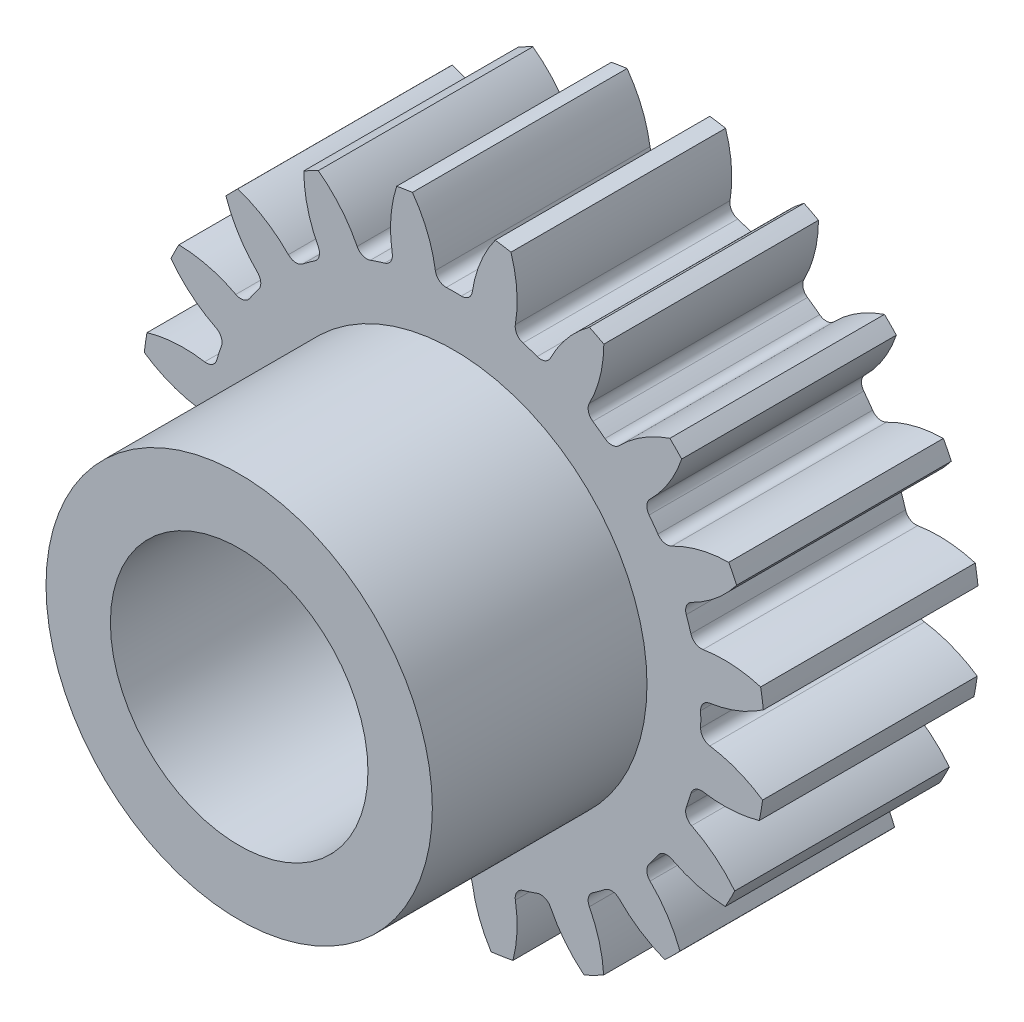
SolidWorks part; units mm, degrees
ref_plane "Front Plane" through (0, 0, 0) normal (0, 0, 1) x (1, 0, 0)
ref_plane "Top Plane" through (0, 0, 0) normal (0, 1, 0) x (1, 0, 0)
ref_plane "Right Plane" through (0, 0, 0) normal (1, 0, 0) x (0, 0, -1)
sketch "Sketch1" plane through (0, 0, 0) normal (0, 0, 1) x (1, 0, 0)
  circle A0 centre (0, 0) radius 3.63
  dimension "D1" = 7.26
extrude "Boss-Extrude1" add sketch "Sketch1" along normal blind 2.5
sketch "Sketch2" plane through (0, 0, 0) normal (0, 0, 1) x (1, 0, 0)
  line L0 (0, 47.3598) -> (0, -34.7567) construction
  line L1 (-0.2027, 2.8307) -> (0, 0) construction
  line L2 (0, 2.4405) -> (-2.4728, 9.2343) construction
  arc A0 (0.4819, 3.5979) -> (-0.4819, 3.5979) centre (0, 0) ccw
  arc A1 (0.3087, 3.2855) -> (-0.3087, 3.2855) centre (0, 0) ccw construction
  arc A2 (0.2027, 2.8307) -> (-0.2027, 2.8307) centre (0, 0) ccw
  arc A3 (-0.4819, 3.5979) -> (-0.2027, 2.8307) centre (-1.6885, 2.7243) cw
  arc A4 (0.4819, 3.5979) -> (0.2027, 2.8307) centre (1.6885, 2.7243) ccw
  point P12 (-0.2888, 3.2338)
  dimension "D1" = 7.26
  dimension "D2" = 6.6
  dimension "D3" = 0.792
  dimension "D4" = 20
  dimension "D5" = 0.6174
extrude "Cut-Extrude1" cut sketch "Sketch2" along normal blind 2.5
fillet "Fillet1" radius 0.1254 2 edges at (0.2027, 2.8307, 1.25) (-0.2027, 2.8307, 1.25)
pattern_circular "CirPattern1" count 20 over 360 about axis through (0, -0.0383, 0) along (0, 0, 1) of "Fillet1", "Cut-Extrude1"
sketch "Sketch3" plane through (0, 0, 2.5) normal (0, 0, 1) x (1, 0, 0)
  line L1 (-5.3522, -1.5) -> (6.9632, -1.5) construction
  line L2 (-4.7981, 1) -> (6.9632, 1) construction
  line L4 (-1.118, 1) -> (1.118, 1)
  arc A0 (-1.118, 1) -> (1.118, 1) centre (0, 0) ccw
  dimension "D1" = 3
  dimension "D2" = 2.5
extrude "Cut-Extrude2" cut sketch "Sketch3" against normal blind 2.5
sketch "Sketch4" plane through (0, 0, 2.5) normal (0, 0, 1) x (1, 0, 0)
  circle A0 centre (0, 0) radius 2.25
  circle A1 centre (0, 0) radius 1.5
  dimension "D1" = 3
  dimension "D2" = 4.5
extrude "Boss-Extrude2" add sketch "Sketch4" along normal blind 2.5
equation "\"No. of Teeth\"= 20"
equation "\"Module\" = 0.33"
equation "\"Bore Diameter\"= 3"
equation "\"Pressure Angle\"= 20"
equation "\"Outer Diameter\"= ( \"No. of Teeth\" + 2 ) * \"Module\""
equation "\"Pitch Diameter\"= \"No. of Teeth\" * \"Module\""
equation "\"Backlash\"= 0.3 * \"Module\""
equation "\"Arc Length\"= ( ( \"Module\" * pi ) / 2 ) + \"Backlash\""
equation "\"Fillet Radius\"= 0.38 * \"Module\""
equation "\"Tooth Depth\"= IIF ( \"Module\" <= 1.25 , 2.4 * \"Module\" , 2.25 * \"Module\" )"
equation "\"D1@Sketch1\"=\"Outer Diameter\""
equation "\"Gear\"= 2.5"
equation "\"D1@Boss-Extrude1\"=\"Gear\""
equation "\"D1@Sketch2\"=\"Outer Diameter\""
equation "\"D2@Sketch2\"=\"Pitch Diameter\""
equation "\"D3@Sketch2\"=\"Tooth Depth\""
equation "\"D4@Sketch2\"=\"Pressure Angle\""
equation "\"D5@Sketch2\"=\"Arc Length\""
equation "\"D1@Cut-Extrude1\"=\"Gear\""
equation "\"D1@Fillet1\"=\"Fillet Radius\""
equation "\"D1@CirPattern1\"=\"No. of Teeth\""
equation "\"D1@Sketch3\"=\"Bore Diameter\""
equation "\"D Cut\"= 2.5"
equation "\"D2@Sketch3\"=\"D Cut\""
equation "\"D1@Cut-Extrude2\"=\"Gear\""
equation "\"D1@Sketch4\"=\"Bore Diameter\""
